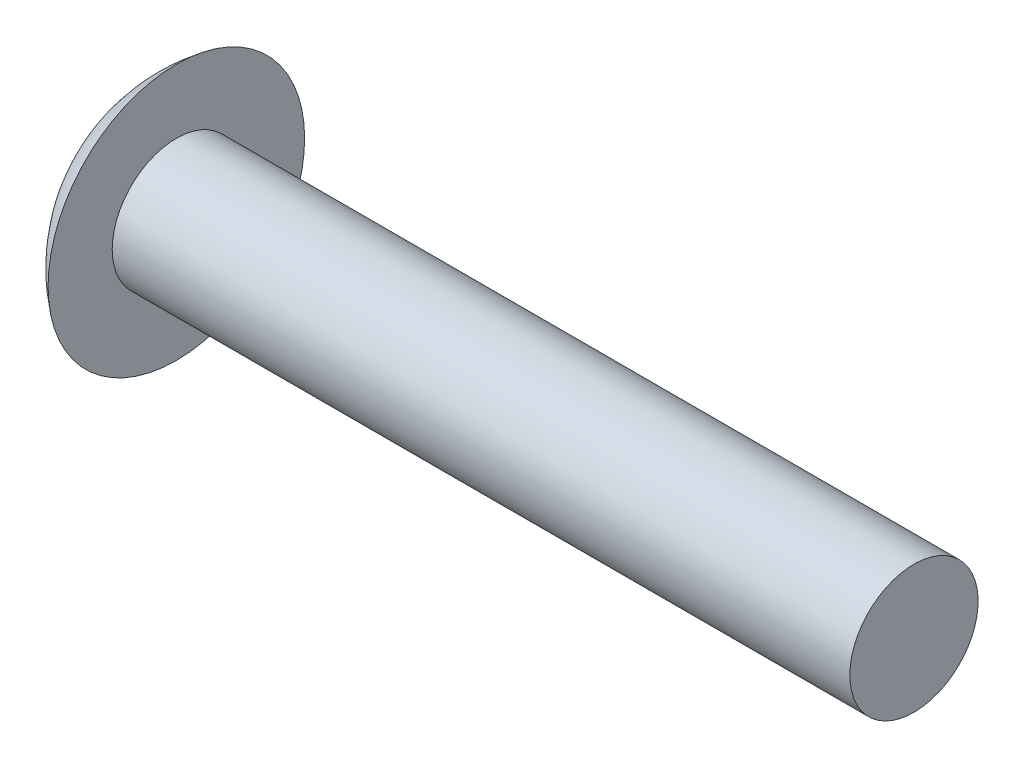
SolidWorks part; units mm, degrees
ref_plane "Front Plane" through (0, 0, 0) normal (0, 0, 1) x (1, 0, 0)
ref_plane "Top Plane" through (0, 0, 0) normal (0, 1, 0) x (1, 0, 0)
ref_plane "Right Plane" through (0, 0, 0) normal (1, 0, 0) x (0, 0, -1)
sketch "Sketch1" plane through (0, 0, 0) normal (0, 0, 1) x (1, 0, 0)
  line L0 (0, 0) -> (25, 0)
  line L1 (25, 0) -> (25, 2)
  line L2 (25, 2) -> (2, 2)
  line L3 (2, 2) -> (2, 4)
  arc A0 (0, 0) -> (2, 4) centre (5, 0) cw
  dimension "D1" = 2
  dimension "D2" = 2
  dimension "D3" = 2
  dimension "D4" = 25
revolve "Revolve1" add sketch "Sketch1" angle 360 about L0
